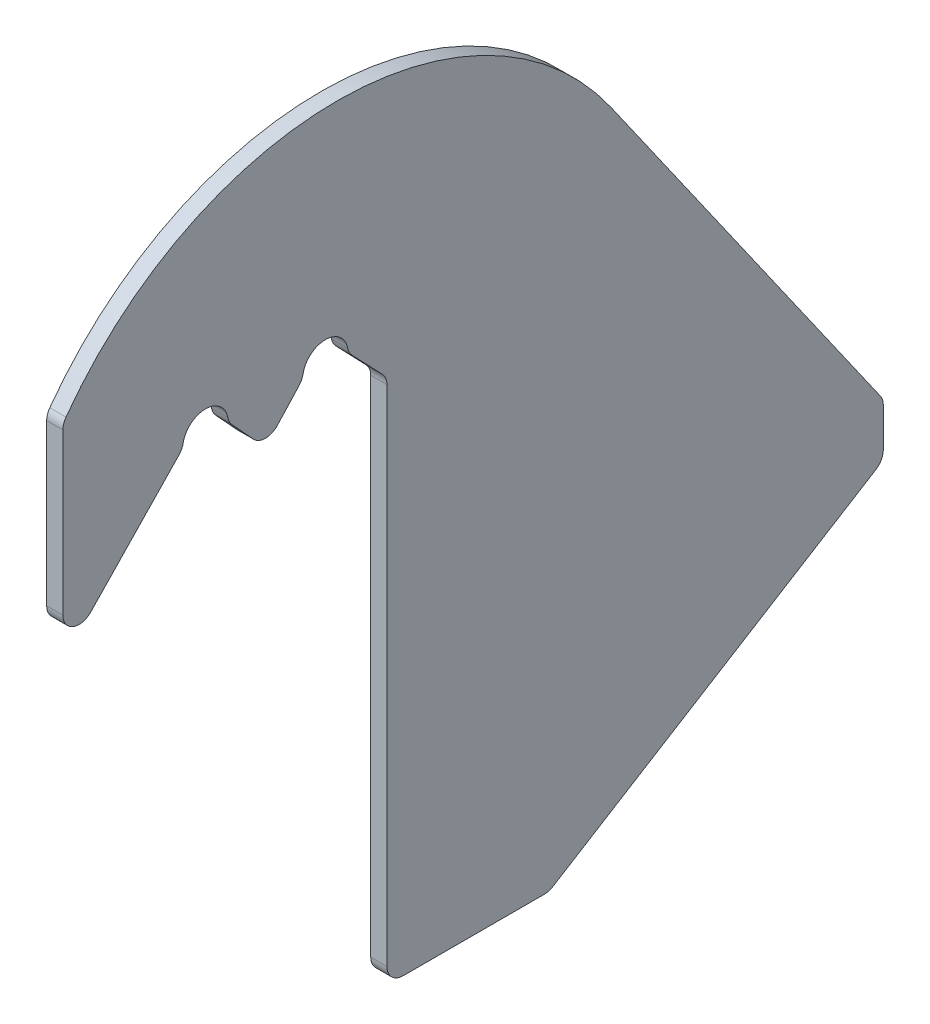
SolidWorks part; units mm, degrees
ref_plane "Front Plane" through (0, 0, 0) normal (0, 0, 1) x (1, 0, 0)
ref_plane "Top Plane" through (0, 0, 0) normal (0, 1, 0) x (1, 0, 0)
ref_plane "Right Plane" through (0, 0, 0) normal (1, 0, 0) x (0, 0, -1)
sketch "Sketch1" plane through (0, 0, 0) normal (1, 0, 0) x (0, 0, -1)
  line L0 (0, 38.1) -> (52.4192, 38.1)
  line L1 (0, 34.925) -> (52.4192, 34.925)
  line L2 (-63.5, 88.9) -> (-25.4, 88.9)
  line L4 (0, 0) -> (0, 88.9)
  line L7 (0, 88.9) -> (-63.5, 88.9)
  line L12 (0, 0) -> (-25.4, 0)
  line L13 (0, 0) -> (0, 88.9)
  line L14 (0, 88.9) -> (-25.4, 88.9)
  line L15 (-25.4, 0) -> (-25.4, 88.9)
  line L17 (0, 101.6) -> (-63.5, 101.6)
  line L23 (-44.45, 88.9) -> (-44.45, 101.6) construction
  line L24 (-31.496, 88.9) -> (-25.4, 82.55)
  line L25 (-63.5, 101.6) -> (-63.5, 82.55)
  line L26 (-63.5, 82.55) -> (-25.4, 82.55) construction
  line L27 (-50.292, 88.9) -> (-44.45, 82.55)
  line L28 (-44.45, 82.55) -> (-38.608, 88.9)
  line L29 (-44.45, 88.9) -> (-44.45, 82.55) construction
  line L30 (-63.5, 82.55) -> (-57.404, 88.9)
  line L31 (52.4192, 38.1) -> (52.4192, 34.925)
  line L32 (0, 88.9) -> (0, 101.6)
  line L37 (-63.5, 101.6) -> (-76.2, 101.6)
  line L39 (0, 38.1) -> (0, 101.6)
  line L42 (-76.2, 101.6) -> (-76.2, 69.3208)
  line L43 (-76.2, 69.3208) -> (-63.5, 82.55)
  line L44 (52.4192, 32.385) -> (52.4192, 40.64)
  line L45 (0, 34.925) -> (-3.175, 34.925)
  line L46 (0, 34.925) -> (0, 88.9)
  line L47 (0, 88.9) -> (-3.175, 88.9)
  line L48 (-3.175, 34.925) -> (-3.175, 88.9)
  line L49 (52.4192, 32.385) -> (0, 0)
  line L50 (52.4192, 40.64) -> (9.7346, 101.6)
  line L51 (-31.496, 88.9) -> (-25.4, 69.3208)
  line L52 (-3.175, 88.9) -> (0, 88.9)
  line L53 (-3.175, 88.9) -> (-3.175, 106.8795)
  line L54 (-3.175, 106.8795) -> (0, 106.8795)
  line L55 (0, 88.9) -> (0, 106.8795)
  arc A0 (-57.404, 88.9) -> (-50.292, 88.9) centre (-53.848, 88.9) cw
  arc A1 (-31.496, 88.9) -> (-38.608, 88.9) centre (-35.052, 88.9) ccw
  arc A3 (9.7346, 101.6) -> (-76.2, 101.6) centre (-33.2327, 71.514) ccw
  point P6 (0, 0)
  point P24 (52.4192, 36.5125)
  dimension "D7" = 3.556
  dimension "D10" = 52.4192
  dimension "D12" = 3.175
  dimension "D2" = 50.8
  dimension "D3" = 88.9
  dimension "D4" = 6.096
  dimension "D5" = 25.4
  dimension "D6" = 6.35
  dimension "D8" = 25.908
  dimension "D9" = 12.7
  dimension "D11" = 3.175
  dimension "D13" = 8.255
  dimension "D14" = 12.7
  dimension "D15" = 55
extrude "Boss-Extrude1" add sketch "Sketch1" along normal blind 2.54 contours L15 L12 L4 L13 L7 | A1 L7 L32 L17 L25 L2 A0 | L42 L43 L25 L37 | L25 L30 L2 | L27 L28 L7 | L7 L24 L15 | L48 L45 L4 L7 | L50 A3 L37 L17 L32 L4 L0 L44 | L31 L0 L4 L1 | L49 L44 L1 L4 | L53 L7 L32 L17 | L17 L55 L54 L53
fillet "Fillet1" radius 2.54 12 edges at (1.27, 0, 25.4) (1.27, 0, 0) (1.27, 32.385, -52.4192) (1.27, 40.64, -52.4192) (1.27, 101.6, 76.2) (1.27, 88.9, 50.292) (1.27, 88.9, 57.404) (1.27, 88.9, 31.496) (1.27, 88.9, 38.608) (1.27, 82.55, 25.4) (1.27, 82.55, 44.45) (1.27, 69.3208, 76.2)
